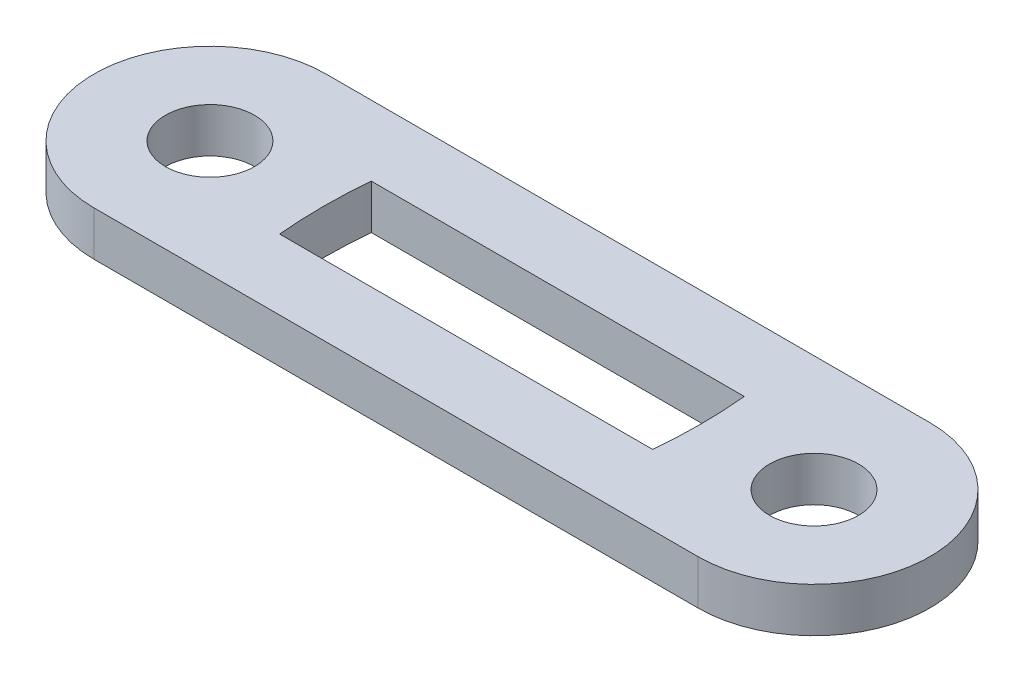
SolidWorks part; units mm, degrees
ref_plane "Front Plane" through (0, 0, 0) normal (0, 0, 1) x (1, 0, 0)
ref_plane "Top Plane" through (0, 0, 0) normal (0, 1, 0) x (1, 0, 0)
ref_plane "Right Plane" through (0, 0, 0) normal (1, 0, 0) x (0, 0, -1)
sketch "Sketch1" plane through (0, 0, 0) normal (0, 1, 0) x (1, 0, 0)
  line L0 (-10.765, 0) -> (10.765, 0) construction
  line L1 (10.765, 4.1337) -> (-10.765, 4.1337)
  line L3 (-10.765, -4.1337) -> (10.765, -4.1337)
  line L4 (6.6473, -1.6337) -> (-6.6473, -1.6337)
  line L5 (-6.6473, 1.6337) -> (6.6473, 1.6337)
  line L6 (10.765, 1.6337) -> (-10.765, 1.6337) construction
  line L7 (-10.765, -1.6337) -> (10.765, -1.6337) construction
  circle A0 centre (10.765, 0) radius 1.5875
  circle A1 centre (-10.765, 0) radius 1.5875
  arc A2 (-10.765, 4.1337) -> (-10.765, -4.1337) centre (-10.765, 0) ccw
  arc A3 (10.765, -4.1337) -> (10.765, 4.1337) centre (10.765, 0) ccw
  circle A4 centre (-9.4564, 0) radius 0.5953 construction
  circle A5 centre (-4.9564, 0) radius 0.5953 construction
  arc A6 (6.6473, 1.6337) -> (6.6473, -1.6337) centre (-10.765, 0) cw
  arc A7 (10.765, -1.6337) -> (10.765, 1.6337) centre (10.765, 0) ccw
  arc A8 (-10.765, 1.6337) -> (-10.765, -1.6337) centre (-10.765, 0) ccw construction
  arc A9 (-6.6473, 1.6337) -> (-6.6473, -1.6337) centre (10.765, 0) ccw
  point P3 (0, 0)
  dimension "D2" = 3.175
  dimension "D3" = 1.1906
  dimension "D4" = 4.5
  dimension "D1" = 21.53
  dimension "D5" = 2.5
  dimension "D6" = 2.5
extrude "Boss-Extrude2" add sketch "Sketch1" along normal mid plane 1.5875
